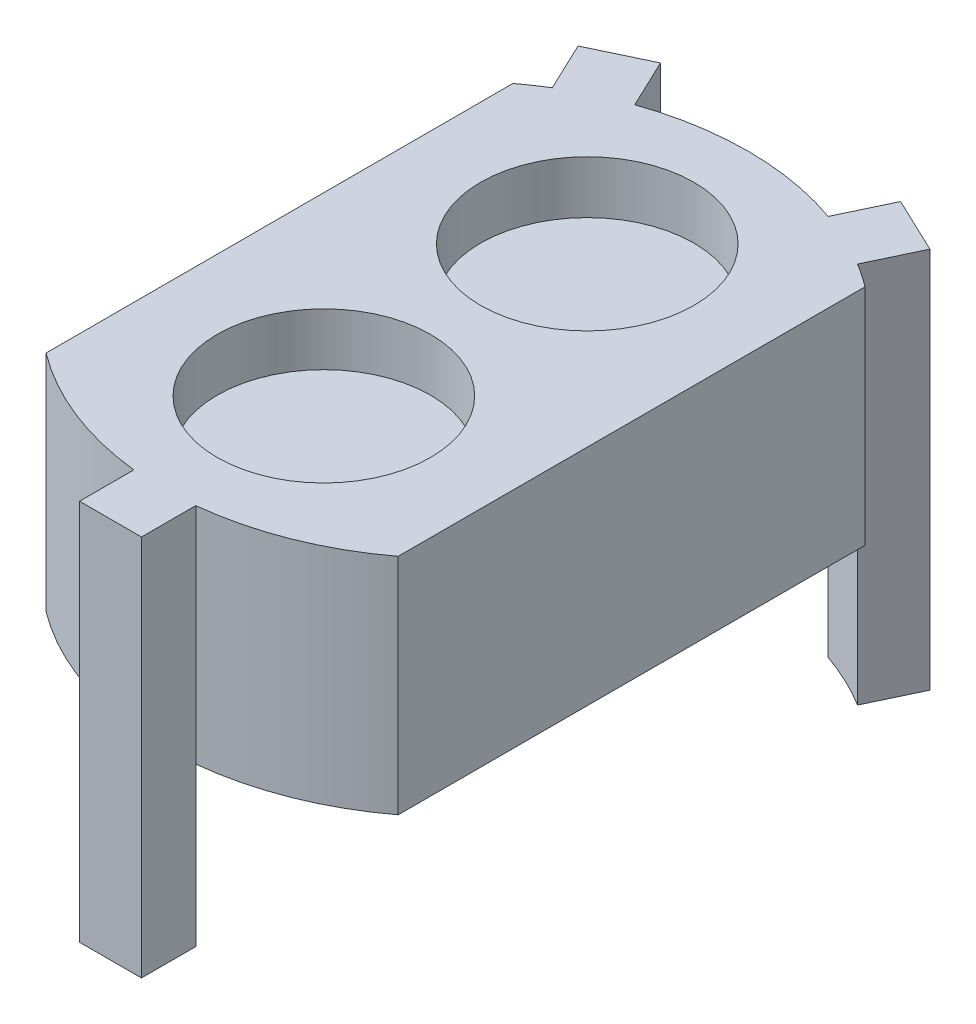
SolidWorks part; units mm, degrees
ref_plane "Front Plane" through (0, 0, 0) normal (0, 0, 1) x (1, 0, 0)
ref_plane "Top Plane" through (0, 0, 0) normal (0, 1, 0) x (1, 0, 0)
ref_plane "Right Plane" through (0, 0, 0) normal (1, 0, 0) x (0, 0, -1)
sketch "Sketch1" plane through (0, 0, 0) normal (0, 1, 0) x (1, 0, 0)
  line L0 (-1.175, 0) -> (1.175, 0) construction
  line L1 (0, 2.74) -> (0, -2.74) construction
  line L2 (-1.175, 0) -> (-1.175, -13.1) construction
  line L3 (1.175, 0) -> (1.175, -13.1) construction
  line L4 (0, -2.74) -> (6.6791, 11.3305) construction
  line L5 (0, 2.74) -> (4.5562, 12.3382) construction
  line L6 (0, 2.74) -> (-4.5562, 12.3382) construction
  line L7 (0, -2.74) -> (-6.6791, 11.3305) construction
  point P6 (0, 0)
  point P9 (0, 0)
  dimension "D2" = 2.35
  dimension "D3" = 13.1
  dimension "D4" = 13.1
  dimension "D5" = 154.607
  dimension "D6" = 154.607
  dimension "D7" = 154.607
  dimension "D8" = 154.607
  dimension "D9" = 5.48
  dimension "D10" = 15.5753
  dimension "D11" = 10.6247
  dimension "D12" = 15.5753
  dimension "D13" = 10.6247
sketch "Sketch2" plane through (0, 0, 0) normal (0, 1, 0) x (1, 0, 0)
  line L16 (-5.7947, 9.4674) -> (-6.6791, 11.3305)
  line L28 (-6.6791, 11.3305) -> (-4.5562, 12.3382)
  line L33 (-4.5562, 12.3382) -> (-3.6718, 10.4751)
  line L44 (3.6718, 10.4751) -> (4.5562, 12.3382)
  line L46 (4.5562, 12.3382) -> (6.6791, 11.3305)
  line L49 (6.6791, 11.3305) -> (5.7947, 9.4674)
  line L56 (1.175, -11.0376) -> (1.175, -13.1)
  line L57 (1.175, -13.1) -> (-1.175, -13.1)
  line L58 (-1.175, -13.1) -> (-1.175, -11.0376)
  arc A12 (-5.7947, 9.4674) -> (-1.175, -11.0376) centre (0, 0) ccw
  arc A13 (3.6718, 10.4751) -> (-3.6718, 10.4751) centre (0, 0) ccw
  arc A14 (1.175, -11.0376) -> (5.7947, 9.4674) centre (0, 0) ccw
  dimension "D1" = 22.2
extrude "Boss-Extrude2" add sketch "Sketch2" along normal blind 14.5
sketch "Sketch3" plane through (0, 0, 0) normal (0, -1, 0) x (1, 0, 0)
  line L0 (-1.175, 0) -> (1.175, 0) construction
  circle A0 centre (0, 0) radius 11.1
  dimension "D1" = 22.2
extrude "Cut-Extrude1" cut sketch "Sketch3" against normal blind 6
sketch "Sketch5" plane through (0, 14.5, 0) normal (0, 1, 0) x (1, 0, 0)
  line L0 (0, 5) -> (0, -5) construction
  circle A0 centre (0, 5) radius 4.05
  circle A1 centre (0, -5) radius 4.05
  point P4 (0, 0)
  dimension "D2" = 8.1
  dimension "D3" = 8.1
  dimension "D1" = 10
extrude "Cut-Extrude2" cut sketch "Sketch5" against normal blind 2
sketch "Sketch6" plane through (0, 0, 0) normal (0, 1, 0) x (1, 0, 0)
  line L0 (-8.8946, 0) -> (8.8946, 0) construction
  line L2 (6.6841, 11.1) -> (11.105, 11.1)
  line L3 (6.6841, 11.1) -> (6.6841, -11.1)
  line L4 (6.6841, -11.1) -> (11.105, -11.1)
  line L5 (11.105, 11.1) -> (11.105, -11.1)
  line L6 (6.6841, 11.1) -> (11.105, -11.1) construction
  line L7 (6.6841, -11.1) -> (11.105, 11.1) construction
  line L8 (-11.105, 11.1) -> (-6.6841, 11.1)
  line L9 (-11.105, 11.1) -> (-11.105, -11.1)
  line L10 (-11.105, -11.1) -> (-6.6841, -11.1)
  line L11 (-6.6841, 11.1) -> (-6.6841, -11.1)
  line L12 (-11.105, 11.1) -> (-6.6841, -11.1) construction
  line L13 (-11.105, -11.1) -> (-6.6841, 11.1) construction
  point P4 (0, 0)
  point P8 (0, 0)
  dimension "D1" = 17.7891
  dimension "D2" = 4.4209
  dimension "D3" = 4.4209
  dimension "D4" = 22.2
  dimension "D5" = 22.2
extrude "Cut-Extrude4" cut sketch "Sketch6" along normal through all
equation "\"radius\" = 11.1mm"
equation "\"distance_b_spokes\" = 9.52mm"
equation "\"spoke_fitter_length\"= 2.35mm"
equation "\"spoke_fitter_height\"= 6mm"
equation "\"spoke_fitter_outcrop\"= 2mm"
equation "\"spoke_angle\"= arcsin ( \"distance_b_spokes\" / ( \"radius\" * 2 ) )"
equation "\"D2@Sketch1\"=\"spoke_fitter_length\""
equation "\"D3@Sketch1\"=\"radius\"+\"spoke_fitter_outcrop\""
equation "\"D4@Sketch1\"=\"radius\"+\"spoke_fitter_outcrop\""
equation "\"D5@Sketch1\"=180 - \"spoke_angle\""
equation "\"D6@Sketch1\"=180 - \"spoke_angle\""
equation "\"D7@Sketch1\"=180 - \"spoke_angle\""
equation "\"D8@Sketch1\"=180 - \"spoke_angle\""
equation "\"D9@Sketch1\"=\"spoke_fitter_length\"/sin(\"spoke_angle\")"
equation "\"D10@Sketch1\"=\"radius\"+\"spoke_fitter_outcrop\"+\"spoke_fitter_length\"/(2*tan(\"spoke_angle\"))"
equation "\"D12@Sketch1\"=\"radius\"+\"spoke_fitter_outcrop\"+\"spoke_fitter_length\"/(2*tan(\"spoke_angle\"))"
equation "\"D13@Sketch1\"=\"radius\"+\"spoke_fitter_outcrop\"-\"spoke_fitter_length\"/(2*tan(\"spoke_angle\"))"
equation "\"D1@Boss-Extrude2\"=\"spoke_fitter_height\"+\"mag_height\"+\"spacer_height\""
equation "\"spacer_height\"= 6.5mm"
equation "\"mag_height\"= 2mm"
equation "\"mag_radius\"= 8.1 / 2mm"
equation "\"D1@Sketch3\"=\"radius\"*2"
equation "\"D1@Cut-Extrude1\"=\"spoke_fitter_height\""
equation "\"mag_space\"= 5 * 2mm"
equation "\"D1@Sketch5\"=\"mag_space\""
equation "\"D2@Sketch5\"=\"mag_radius\"*2"
equation "\"D3@Sketch5\"=\"mag_radius\"*2"
equation "\"D1@Cut-Extrude2\"=\"mag_height\""
equation "\"D1@Sketch6\"=(\"D10@Sketch1\"*cos(90 - \"spoke_angle\")) + \"radius\" + 0.01"
equation "\"D2@Sketch6\"= \"radius\" - (\"D10@Sketch1\"*cos(90 - \"spoke_angle\"))"
equation "\"D3@Sketch6\"= \"radius\" - (\"D10@Sketch1\"*cos(90 - \"spoke_angle\"))"
equation "\"D4@Sketch6\"=\"radius\"*2"
equation "\"D5@Sketch6\"=\"radius\"*2"
equation "\"D11@Sketch1\"=\"radius\"+\"spoke_fitter_outcrop\"-\"spoke_fitter_length\"/(2*tan(\"spoke_angle\"))"
equation "\"D1@Sketch2\"=\"radius\"*2"
